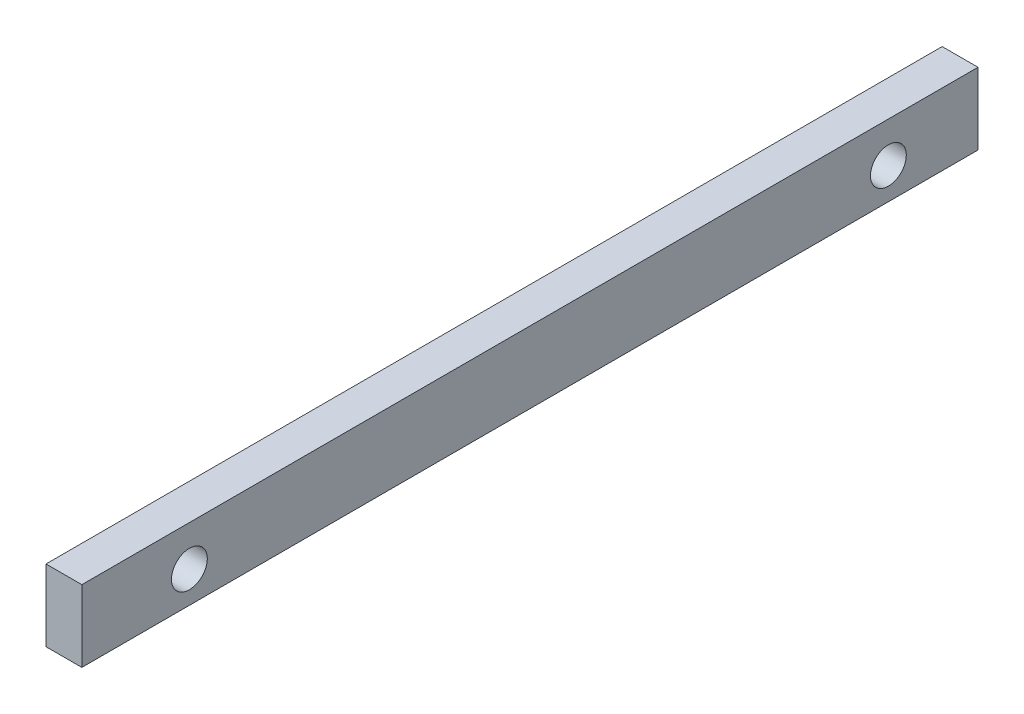
SolidWorks part; units mm, degrees
ref_plane "Front Plane" through (0, 0, 0) normal (0, 0, 1) x (1, 0, 0)
ref_plane "Top Plane" through (0, 0, 0) normal (0, 1, 0) x (1, 0, 0)
ref_plane "Right Plane" through (0, 0, 0) normal (1, 0, 0) x (0, 0, -1)
sketch "Sketch1" plane through (0, 0, 0) normal (1, 0, 0) x (0, 0, -1)
  line L1 (-40.1373, 5.316) -> (59.8627, 5.316)
  line L2 (-40.1373, 5.316) -> (-40.1373, -2.684)
  line L3 (-40.1373, -2.684) -> (59.8627, -2.684)
  line L4 (59.8627, 5.316) -> (59.8627, -2.684)
  circle A0 centre (-28.1373, 0.8275) radius 2
  circle A1 centre (49.8627, 0.8275) radius 2
  dimension "D3" = 80
  dimension "D1" = 100
  dimension "D2" = 8
  dimension "D4" = 10
extrude "Boss-Extrude1" add sketch "Sketch1" along normal blind 4
